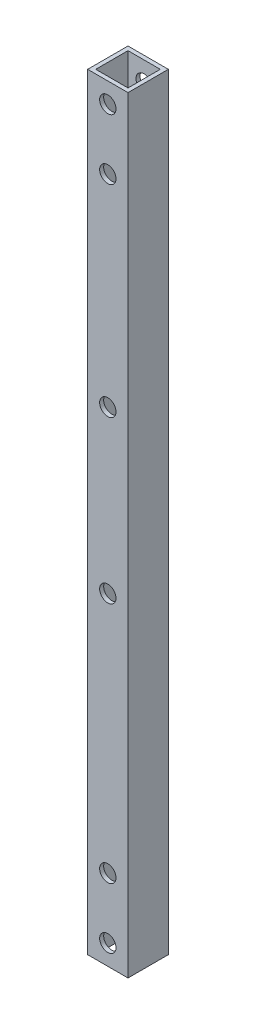
SolidWorks part; units mm, degrees
material "1345 Alloy"
ref_plane "Front Plane" through (0, 0, 0) normal (0, 0, 1) x (1, 0, 0)
ref_plane "Top Plane" through (0, 0, 0) normal (0, 1, 0) x (1, 0, 0)
ref_plane "Right Plane" through (0, 0, 0) normal (1, 0, 0) x (0, 0, -1)
sketch "Sketch1" plane through (0, 0, 0) normal (0, 1, 0) x (1, 0, 0)
  line L1 (-5, 5) -> (5, 5)
  line L2 (-5, 5) -> (-5, -5)
  line L3 (-5, -5) -> (5, -5)
  line L4 (5, 5) -> (5, -5)
  line L5 (-5, 5) -> (5, -5) construction
  line L6 (-5, -5) -> (5, 5) construction
  line L7 (-4, 4) -> (4, 4)
  line L8 (-4, 4) -> (-4, -4)
  line L9 (-4, -4) -> (4, -4)
  line L10 (4, 4) -> (4, -4)
  line L11 (-4, 4) -> (4, -4) construction
  line L12 (-4, -4) -> (4, 4) construction
  point P0 (0, 0)
  point P6 (0, 0)
  dimension "D1" = 10
  dimension "D2" = 10
  dimension "D3" = 8
  dimension "D4" = 8
extrude "Boss-Extrude1" add sketch "Sketch1" along normal blind 190
sketch "Sketch2" plane through (0, 0, 5) normal (0, 0, 1) x (1, 0, 0)
  line L0 (0, 311.3175) -> (0, -13.2043) construction
  line L1 (-5, 190) -> (5, 190) construction
  circle A0 centre (0, 120) radius 2.025
  circle A1 centre (0, 80) radius 2.025
  dimension "D1" = 4.05
  dimension "D2" = 4.05
  dimension "D3" = 40
  dimension "D4" = 70
extrude "Cut-Extrude1" cut sketch "Sketch2" against normal through all
sketch "Sketch3" plane through (0, 0, 5) normal (0, 0, 1) x (1, 0, 0)
  line L0 (0, 309.7003) -> (0, -6.7354) construction
  line L1 (-5, 190) -> (5, 190) construction
  line L2 (-5, 0) -> (5, 0) construction
  circle A0 centre (0, 185) radius 2.025
  circle A1 centre (0, 170) radius 2.025
  circle A2 centre (0, 5) radius 2.025
  circle A3 centre (0, 20) radius 2.025
  dimension "D1" = 4.05
  dimension "D2" = 4.05
  dimension "D3" = 4.05
  dimension "D4" = 4.05
  dimension "D5" = 15
  dimension "D6" = 5
  dimension "D7" = 5
  dimension "D8" = 15
extrude "Cut-Extrude2" cut sketch "Sketch3" against normal through all
